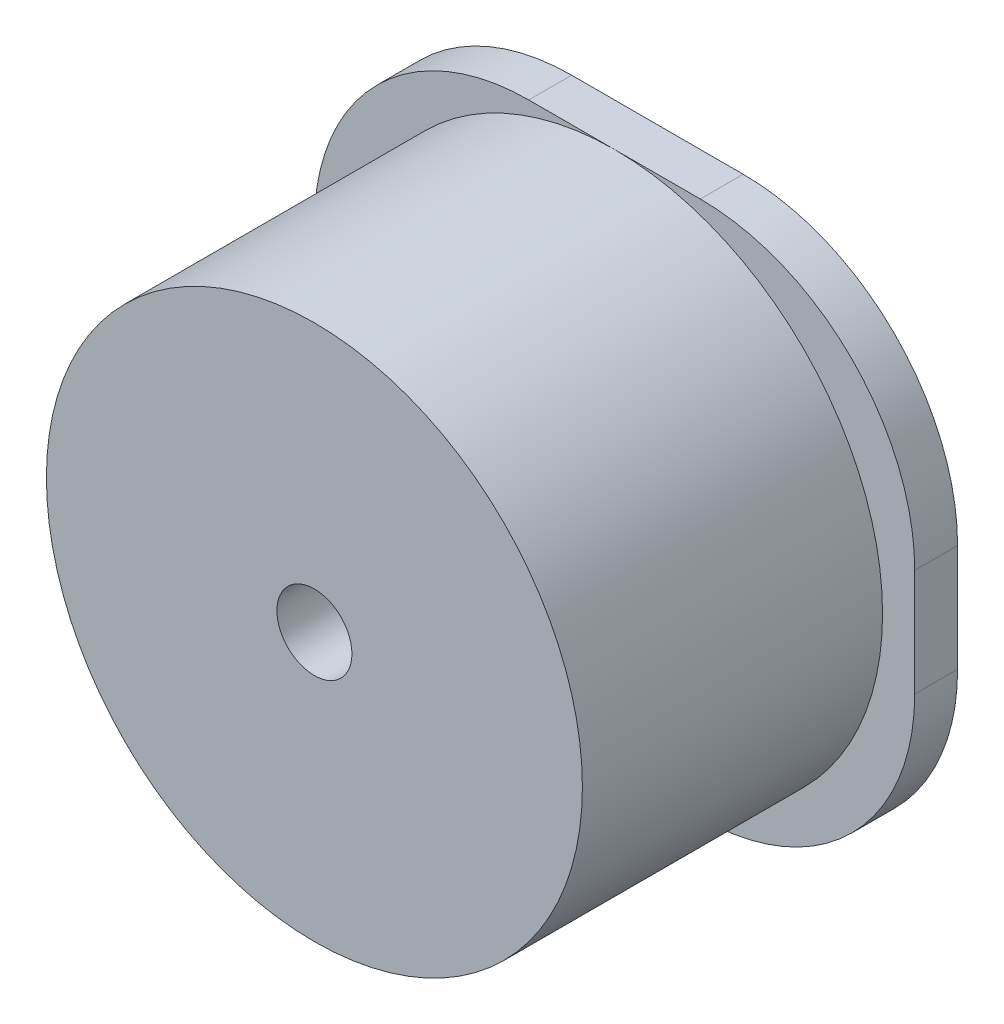
SolidWorks part; units mm, degrees
ref_plane "正面" through (0, 0, 0) normal (0, 0, 1) x (1, 0, 0)
ref_plane "平面" through (0, 0, 0) normal (0, 1, 0) x (1, 0, 0)
ref_plane "右側面" through (0, 0, 0) normal (1, 0, 0) x (0, 0, -1)
sketch "ｽｹｯﾁ1" plane through (0, 0, 0) normal (0, 0, 1) x (1, 0, 0)
  circle A0 centre (0, 0) radius 12.5
  point P3 (0, 0)
  dimension "D1" = 25
extrude "ﾎﾞｽ - 押し出し1" add sketch "ｽｹｯﾁ1" along normal blind 14
sketch "ｽｹｯﾁ2" plane through (0, 0, 14) normal (0, 0, 1) x (1, 0, 0)
  circle A0 centre (0, 0) radius 1.75
  dimension "D1" = 3.5
extrude "ｶｯﾄ - 押し出し1" cut sketch "ｽｹｯﾁ2" against normal blind 6
sketch "ｽｹｯﾁ3" plane through (0, 0, 0) normal (0, 0, -1) x (-1, 0, 0)
  line L1 (-14, 12.5) -> (14, 12.5)
  line L2 (-14, 12.5) -> (-14, -12.5)
  line L3 (-14, -12.5) -> (14, -12.5)
  line L4 (14, 12.5) -> (14, -12.5)
  circle A0 centre (0, 0) radius 12.5 construction
  dimension "D1" = 28
  dimension "D2" = 14
extrude "ﾎﾞｽ - 押し出し2" add sketch "ｽｹｯﾁ3" along normal blind 2
fillet "ﾌｨﾚｯﾄ1" radius 10 4 edges at (-14, -12.5, -1) (14, -12.5, -1) (-14, 12.5, -1) (14, 12.5, -1)
